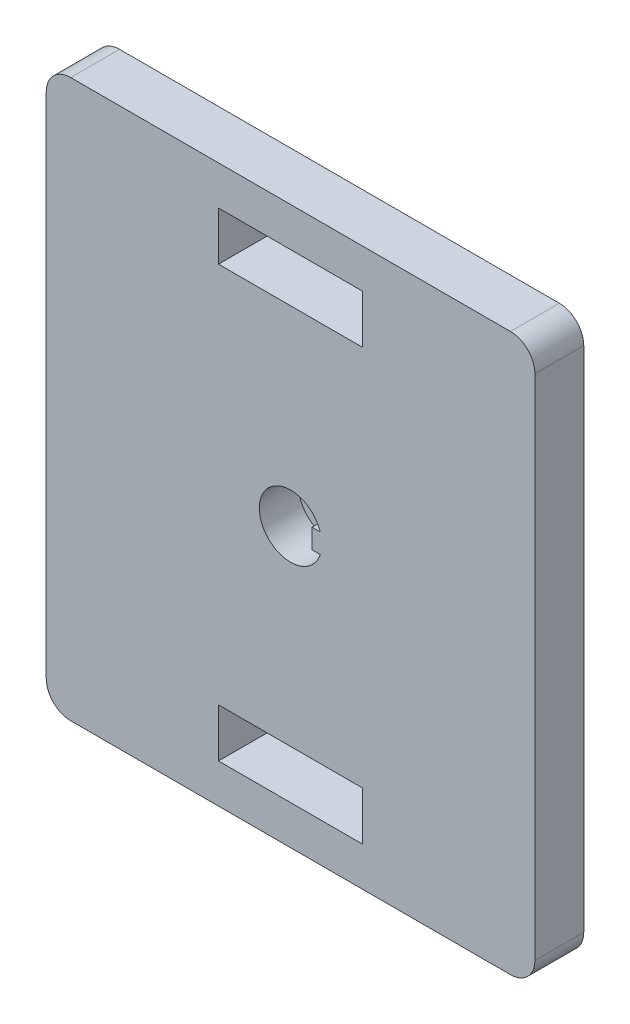
SolidWorks part; units mm, degrees
ref_plane "Ön Düzlem" through (0, 0, 0) normal (0, 0, 1) x (1, 0, 0)
ref_plane "Üst Düzlem" through (0, 0, 0) normal (0, 1, 0) x (1, 0, 0)
ref_plane "Sağ Düzlem" through (0, 0, 0) normal (1, 0, 0) x (0, 0, -1)
ref_plane "Düzlem1" through (0, 0, 10) normal (0, 0, 1) x (1, 0, 0)
sketch "Çizim1" plane through (0, 0, 10) normal (0, 0, 1) x (1, 0, 0)
  line L0 (0, 0) -> (100, 0)
  line L1 (100, 0) -> (100, 114)
  line L2 (100, 114) -> (0, 114)
  line L3 (0, 114) -> (0, 0)
extrude "Yükseklik-Ekstrüzyon1" add sketch "Çizim1" against normal blind 10
sketch "Çizim2" plane through (0, 0, 10) normal (0, 0, 1) x (1, 0, 0)
  line L0 (35.25, 96.05) -> (64.75, 96.05)
  line L1 (64.75, 96.05) -> (64.75, 106)
  line L2 (64.75, 106) -> (35.25, 106)
  line L3 (35.25, 106) -> (35.25, 96.05)
  line L4 (100, 114) -> (0, 114) construction
  line L5 (100, 0) -> (100, 114) construction
  line L6 (0, 114) -> (0, 0) construction
  dimension "D1" = 8
  dimension "D2" = 35.25
  dimension "D3" = 9.95
  dimension "D4" = 35.25
extrude "Kes-Ekstrüzyon1" cut sketch "Çizim2" against normal through all
sketch "Çizim3" plane through (0, 0, 0) normal (0, 0, -1) x (-1, 0, 0)
  line L0 (-35.25, 8) -> (-35.25, 17.95)
  line L1 (-35.25, 17.95) -> (-64.75, 17.95)
  line L2 (-64.75, 17.95) -> (-64.75, 8)
  line L3 (-64.75, 8) -> (-35.25, 8)
  line L4 (-100, 0) -> (-100, 114) construction
  line L5 (0, 0) -> (-100, 0) construction
  line L6 (0, 114) -> (0, 0) construction
  dimension "D1" = 35.25
  dimension "D2" = 9.95
  dimension "D3" = 8
  dimension "D4" = 35.25
extrude "Kes-Ekstrüzyon2" cut sketch "Çizim3" against normal through all
fillet "Radyus1" radius 5 4 edges at (0, 0, 5) (0, 114, 5) (100, 0, 5) (100, 114, 5)
sketch "Çizim14" plane through (0, 0, 10) normal (0, 0, 1) x (1, 0, 0)
  line L0 (35.25, 96.05) -> (64.75, 96.05) construction
  line L1 (54.4, 59) -> (54.4, 55)
  line L4 (0, 109) -> (0, 5) construction
  line L7 (54.4, 59) -> (56.0795, 59)
  line L8 (54.4, 55) -> (56.0795, 55)
  arc A0 (56.0795, 59) -> (56.0795, 55) centre (50, 57) ccw
  point P7 (54.4, 57)
  dimension "D1" = 39.05
  dimension "D2" = 50
extrude "Kes-Ekstrüzyon3" cut sketch "Çizim14" against normal blind 8 contours A0 L8 L1 L7
